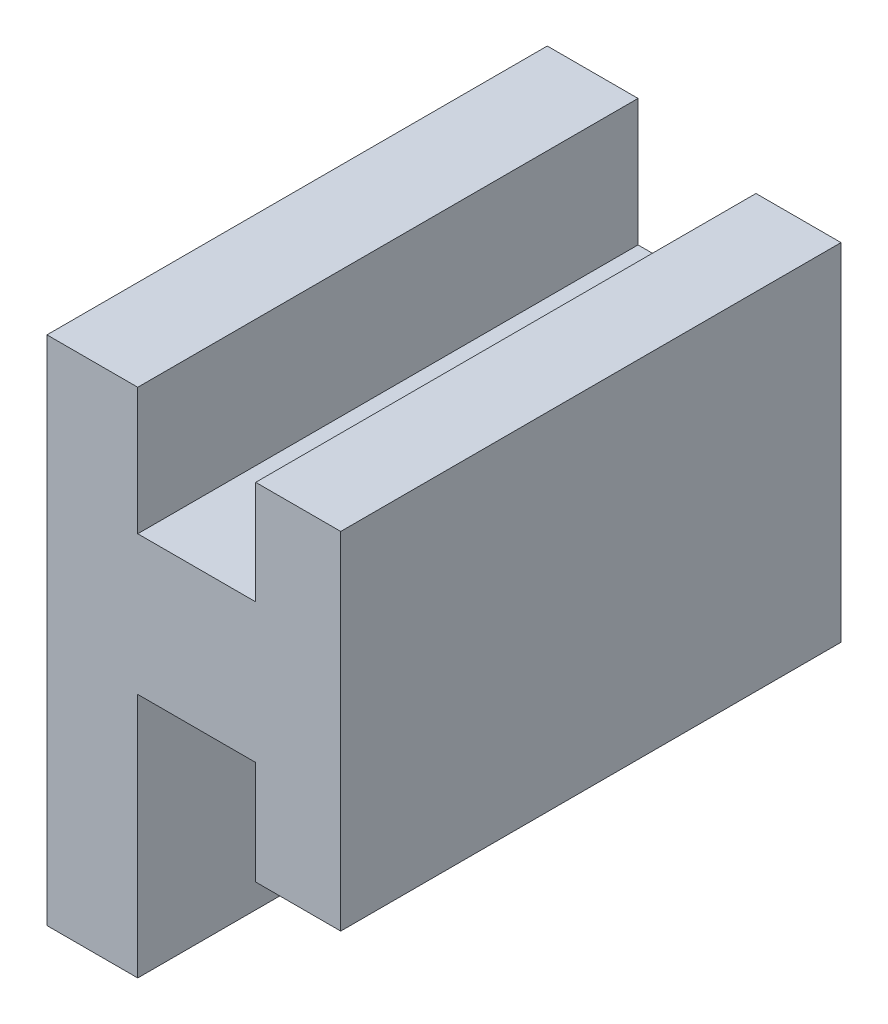
SolidWorks part; units mm, degrees
ref_plane "Front Plane" through (0, 0, 0) normal (0, 0, 1) x (1, 0, 0)
ref_plane "Top Plane" through (0, 0, 0) normal (0, 1, 0) x (1, 0, 0)
ref_plane "Right Plane" through (0, 0, 0) normal (1, 0, 0) x (0, 0, -1)
sketch "Sketch2" plane through (0, 0, 0) normal (0, 0, 1) x (1, 0, 0)
  line L0 (-32, -20.059) -> (-34.1144, -20.059) construction
  line L1 (-34.1144, -20.059) -> (-34.1144, -9.533) construction
  line L2 (-34.1144, -9.533) -> (-32, -9.533) construction
  line L3 (-32, -8.1732) -> (-32, -12.0692) construction
  line L4 (-32, -9.533) -> (-32, -12.0692) construction
  line L5 (-32, -12.0692) -> (-29.9428, -12.0692) construction
  line L6 (-29.9428, -12.0692) -> (-29.9428, -10) construction
  line L7 (-29.9428, -12.0692) -> (-29.9428, -10) construction
  line L8 (-29.9428, -10) -> (-27.9428, -10) construction
  line L9 (-27.9428, -10) -> (-27.9428, -17.2189) construction
  line L10 (-27.9428, -17.2189) -> (-29.9428, -17.2189) construction
  line L11 (-29.9428, -17.2189) -> (-29.9428, -15.1497) construction
  line L12 (-29.9428, -15.1497) -> (-32, -15.1497) construction
  line L13 (-32, -15.1497) -> (-32, -20.059) construction
  line L14 (-29.9428, -15.1497) -> (-32, -15.1497) construction
  line L15 (-32, -15.1497) -> (-32, -20.059) construction
  line L16 (-32.15, -9.683) -> (-32.15, -12.2192)
  line L17 (-32.15, -12.2192) -> (-29.7928, -12.2192)
  line L18 (-29.7928, -12.2192) -> (-29.7928, -10.15)
  line L19 (-29.7928, -10.15) -> (-28.0928, -10.15)
  line L20 (-28.0928, -10.15) -> (-28.0928, -17.0689)
  line L21 (-28.0928, -17.0689) -> (-29.7928, -17.0689)
  line L22 (-29.7928, -17.0689) -> (-29.7928, -14.9997)
  line L23 (-29.7928, -14.9997) -> (-32.15, -14.9997)
  line L24 (-32.15, -14.9997) -> (-32.15, -19.909)
  line L25 (-32.15, -19.909) -> (-33.9644, -19.909)
  line L26 (-33.9644, -19.909) -> (-33.9644, -9.683)
  line L27 (-33.9644, -9.683) -> (-32.15, -9.683)
  dimension "D1" = 0.15
extrude "Boss-Extrude1" add sketch "Sketch2" against normal blind 10
